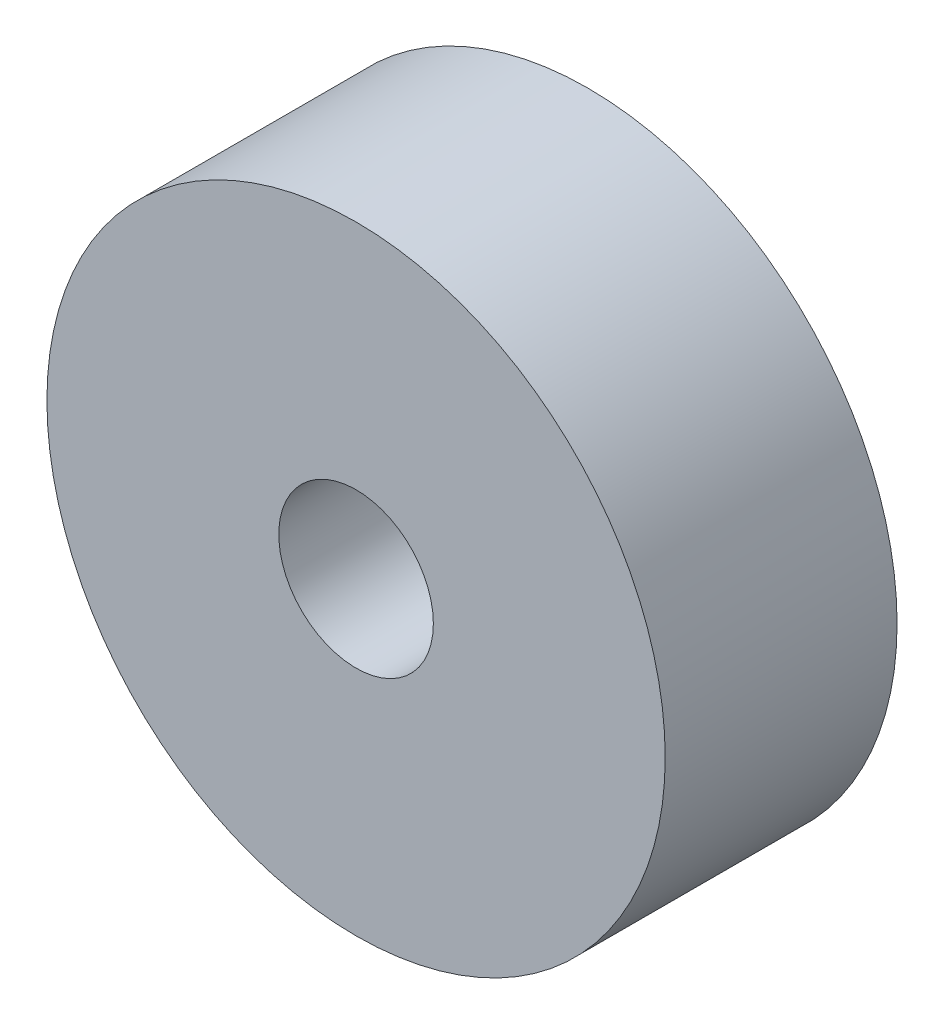
SolidWorks part; units mm, degrees
ref_plane "Front Plane" through (0, 0, 0) normal (0, 0, 1) x (1, 0, 0)
ref_plane "Top Plane" through (0, 0, 0) normal (0, 1, 0) x (1, 0, 0)
ref_plane "Right Plane" through (0, 0, 0) normal (1, 0, 0) x (0, 0, -1)
sketch "Sketch1" plane through (0, 0, 0) normal (0, 0, 1) x (1, 0, 0)
  circle A0 centre (0, 0) radius 101.6
  circle A1 centre (0, 0) radius 25.4
extrude "Boss-Extrude2" add sketch "Sketch1" against normal blind 76.2
